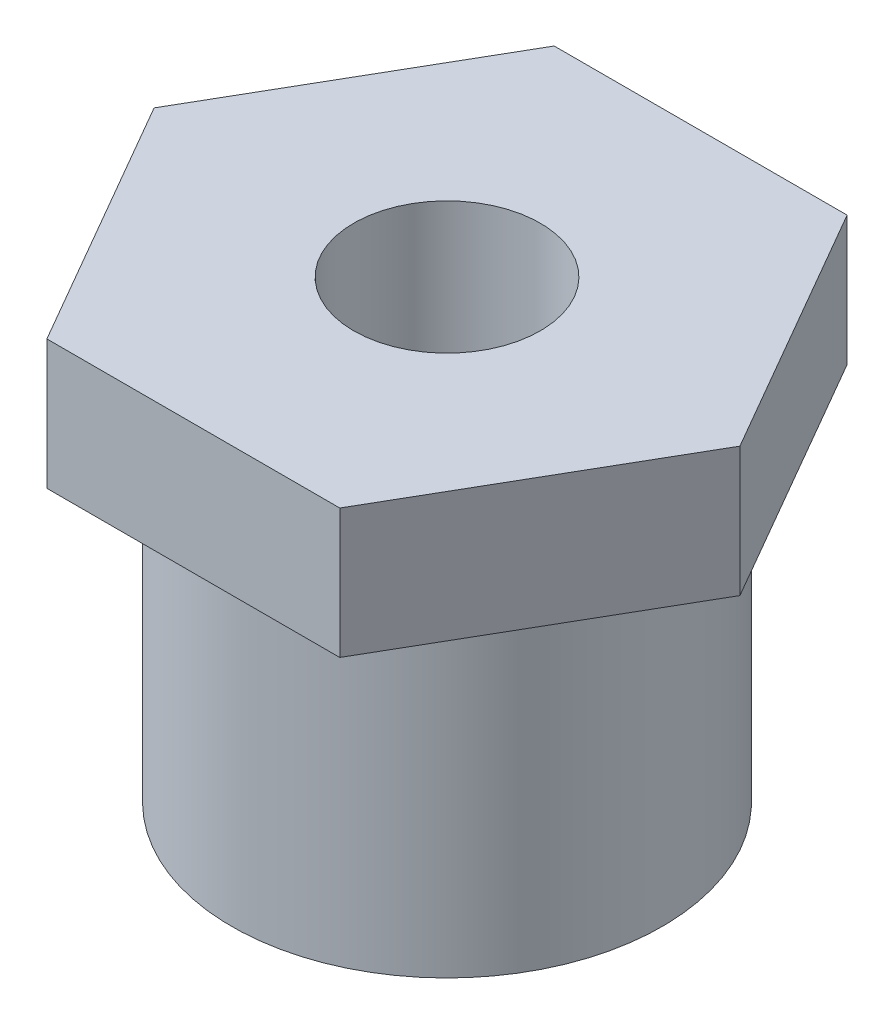
SolidWorks part; units mm, degrees
material "1060 Alloy"
ref_plane "Front Plane" through (0, 0, 0) normal (0, 0, 1) x (1, 0, 0)
ref_plane "Top Plane" through (0, 0, 0) normal (0, 1, 0) x (1, 0, 0)
ref_plane "Right Plane" through (0, 0, 0) normal (1, 0, 0) x (0, 0, -1)
sketch "Sketch1" plane through (0, 0, 0) normal (0, 1, 0) x (1, 0, 0)
  line L1 (18.2209, 0) -> (9.1104, 15.7797)
  line L2 (9.1104, 15.7797) -> (-9.1104, 15.7797)
  line L3 (-9.1104, 15.7797) -> (-18.2209, 0)
  line L4 (-18.2209, 0) -> (-9.1104, -15.7797)
  line L5 (-9.1104, -15.7797) -> (9.1104, -15.7797)
  line L6 (9.1104, -15.7797) -> (18.2209, 0)
  circle A0 centre (0, 0) radius 15.7797 construction
  dimension "D1" = 31.5595
extrude "Boss-Extrude1" add sketch "Sketch1" along normal blind 8.0518
sketch "Sketch2" plane through (0, 0, 0) normal (0, -1, 0) x (-1, 0, 0)
  circle A0 centre (0, 0) radius 13.3922
  dimension "D1" = 26.7843
extrude "Boss-Extrude2" add sketch "Sketch2" along normal blind 20.2438
sketch "Sketch3" plane through (0, 8.0518, 0) normal (0, 1, 0) x (1, 0, 0)
  circle A0 centre (0, 0) radius 5.8039
  dimension "D1" = 11.6078
extrude "Cut-Extrude1" cut sketch "Sketch3" against normal blind 10.3886
sketch "Sketch4" plane through (0, -20.2438, 0) normal (0, -1, 0) x (1, 0, 0)
  circle A0 centre (0, 0) radius 8.0137
  dimension "D1" = 16.0274
extrude "Cut-Extrude2" cut sketch "Sketch4" against normal blind 16.1925
sketch "Sketch5" plane through (0, 0, 0) normal (0, 0, 1) x (1, 0, 0)
  line L9 (0, -2.3368) -> (0, -4.0513)
  line L10 (5.8039, -2.3368) -> (-5.8039, -2.3368) construction
  line L11 (-8.0137, -4.0513) -> (8.0137, -4.0513) construction
  line L13 (-5.8039, -2.3368) -> (-8.0137, -4.0513)
  line L14 (-8.0137, -4.0513) -> (0, -4.0513)
  line L15 (-5.8039, -2.3368) -> (0, -2.3368)
revolve "Cut-Revolve4" cut sketch "Sketch5" angle 360 about L9
thread "Thread1" pitch 1.4111 start angle 0, offset 0, length 0, pitch 1.4111, diameter 11.6078
ref_plane "Plane1" through (-5.8039, 8.0518, 0) normal (0, 0, 1) x (-1, 0, 0)
sketch "Thread Profile1" plane through (-5.8039, 8.0518, 0) normal (0, 0, 1) x (-1, 0, 0)
  line L0 (0, 0) -> (0, 1.4111) construction
  line L1 (0, 0) -> (0.7638, 0.441)
  line L2 (0.7638, 0.441) -> (0.7638, 0.6174)
  line L3 (0.7638, 0.6174) -> (0, 1.0583)
  line L4 (0.7638, 0.5292) -> (0, 0.5292) construction
  line L11 (0, 0) -> (0, 1.0583)
  point P2 (0, 0)
  dimension "Pitch" = 1.4111
  dimension "Profile_Angle" = 60
  dimension "Profile_Land" = 0.1764
  dimension "Profile_Height" = 0.7638
thread "Thread2" pitch 1.5875 start angle 0, offset 0, length 0, pitch 1.5875, diameter 26.7843
ref_plane "Plane3" through (-13.3922, 0, 0) normal (0, 0, 1) x (-1, 0, 0)
sketch "Thread Profile3" plane through (-13.3922, 0, 0) normal (0, 0, 1) x (-1, 0, 0)
  line L0 (0, 0) -> (0, 1.5875) construction
  line L1 (0, 0) -> (0.8593, 0.4961)
  line L2 (0.8593, 0.4961) -> (0.8593, 0.6945)
  line L3 (0.8593, 0.6945) -> (0, 1.1906)
  line L4 (0.8593, 0.5953) -> (0, 0.5953) construction
  line L11 (0, 0) -> (0, 1.1906)
  point P2 (0, 0)
  dimension "Pitch" = 1.5875
  dimension "Profile_Angle" = 60
  dimension "Profile_Land" = 0.1984
  dimension "Profile_Height" = 0.8593
